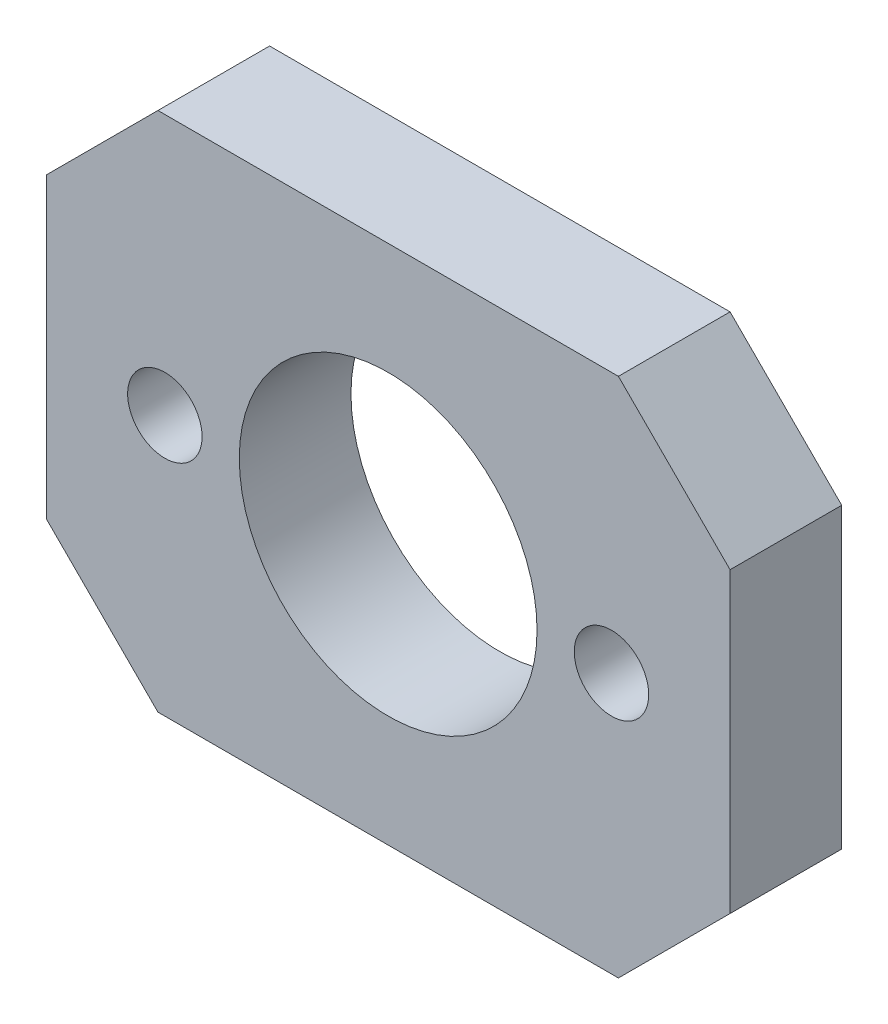
SolidWorks part; units mm, degrees
ref_plane "Front Plane" through (0, 0, 0) normal (0, 0, 1) x (1, 0, 0)
ref_plane "Top Plane" through (0, 0, 0) normal (0, 1, 0) x (1, 0, 0)
ref_plane "Right Plane" through (0, 0, 0) normal (1, 0, 0) x (0, 0, -1)
sketch "Sketch1" plane through (0, 0, 0) normal (0, 0, 1) x (1, 0, 0)
  line L1 (-9.186, -7) -> (9.186, -7)
  line L2 (-9.186, -7) -> (-9.186, 7)
  line L3 (-9.186, 7) -> (9.186, 7)
  line L4 (9.186, -7) -> (9.186, 7)
  line L5 (-9.186, -7) -> (9.186, 7) construction
  line L6 (-9.186, 7) -> (9.186, -7) construction
  circle A0 centre (-6, 0) radius 1
  circle A1 centre (6, 0) radius 1
  circle A2 centre (0, 0) radius 4
  point P0 (0, 0)
  dimension "D1" = 6
  dimension "D2" = 6
  dimension "D3" = 2
  dimension "D4" = 2
  dimension "D5" = 8
  dimension "D6" = 14
extrude "Boss-Extrude1" add sketch "Sketch1" along normal blind 3
chamfer "Chamfer1" distance 3 angle 45 4 edges at (-9.186, 7, 1.5) (9.186, 7, 1.5) (-9.186, -7, 1.5) (9.186, -7, 1.5)
